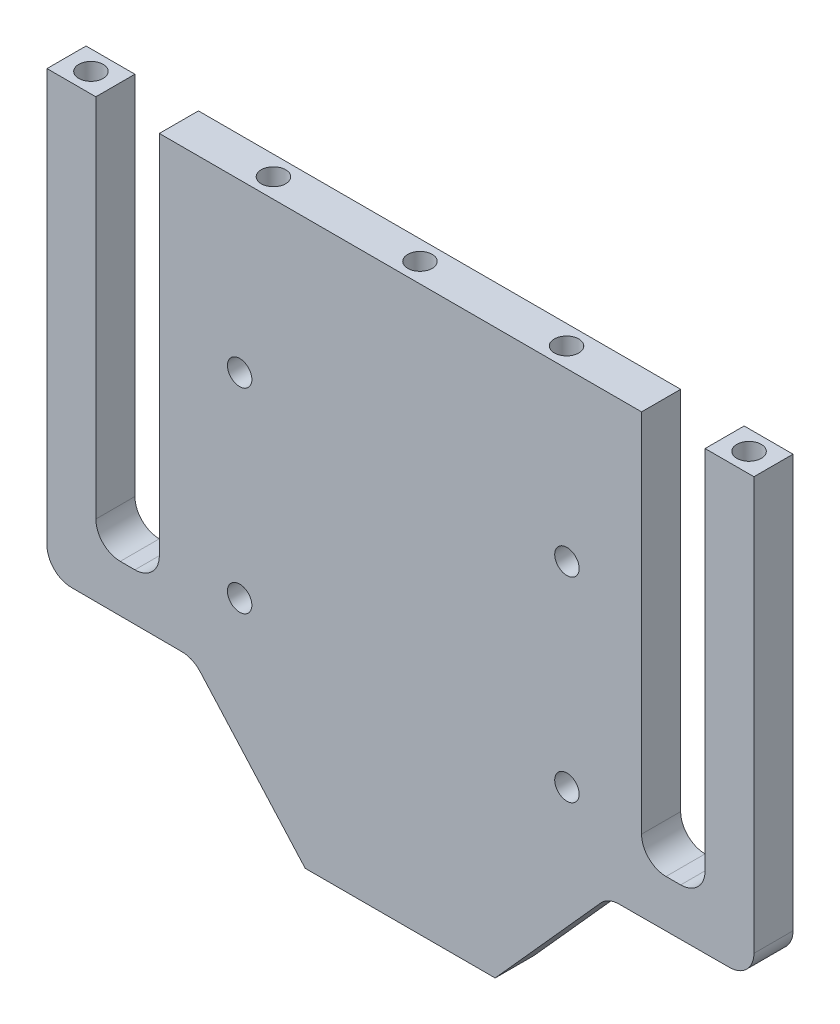
SolidWorks part; units mm, degrees
ref_plane "Front Plane" through (0, 0, 0) normal (0, 0, 1) x (1, 0, 0)
ref_plane "Top Plane" through (0, 0, 0) normal (0, 1, 0) x (1, 0, 0)
ref_plane "Right Plane" through (0, 0, 0) normal (1, 0, 0) x (0, 0, -1)
sketch "Sketch1" plane through (0, 0, 0) normal (0, 0, 1) x (1, 0, 0)
  line L4 (70, 309.9858) -> (85.2992, 309.9858)
  line L6 (43.2101, 271.7903) -> (49.7246, 305.9232)
  line L7 (42.2614, 270.1156) -> (0.0495, 220.7861)
  line L8 (0.0495, 220.7861) -> (42.9, 220.7861) construction
  line L9 (42.9, 220.7861) -> (42.9, 270.8599) construction
  line L10 (96.9829, 220.8599) -> (96.9829, 270.8599) construction
  line L11 (112.4871, 25.7747) -> (89.3829, 25.7747) construction
  line L12 (27.5129, 25.7747) -> (50.5, 25.7747) construction
  line L13 (25.2828, 25.7823) -> (2.6386, 25.8599)
  line L14 (96.6727, 271.7903) -> (90.212, 305.9159)
  line L15 (70, 329.5221) -> (70, -78.2612) construction
  line L18 (50.5, 25.7747) -> (50.5, 0) construction
  line L19 (70, 309.9858) -> (54.636, 309.9858)
  line L20 (135.9829, 220.8599) -> (96.9829, 220.8599) construction
  line L21 (139.9505, 220.7861) -> (135.9829, 220.8599) construction
  line L25 (89.3829, 25.7747) -> (89.3829, 0) construction
  line L27 (89.3829, 0) -> (50.5, 0)
  line L28 (12.6386, 35.4925) -> (15.6386, 35.4925)
  line L35 (127.3614, 35.4925) -> (124.3614, 35.4925)
  line L36 (119.3614, 213.626) -> (132.3614, 213.626)
  line L37 (119.3614, 40.4925) -> (119.3614, 213.626)
  line L38 (132.3614, 213.626) -> (132.3614, 40.4925)
  line L39 (142.3614, 214.274) -> (142.3614, 30.8599)
  line L40 (97.6215, 270.1156) -> (139.9505, 220.7861)
  line L41 (-2.3614, 214.274) -> (-2.3614, 30.8599)
  line L42 (7.6386, 213.626) -> (7.6386, 40.4925)
  line L43 (20.6386, 40.4925) -> (20.6386, 213.626)
  line L44 (20.6386, 213.626) -> (7.6386, 213.626)
  line L45 (28.9972, 24.1103) -> (50.5, 0)
  line L46 (114.7172, 25.7823) -> (137.3614, 25.8599)
  line L47 (89.3829, 0) -> (111.0028, 24.1103)
  arc A1 (42.2614, 270.1156) -> (43.2101, 271.7903) centre (38.4667, 273.3715) ccw
  arc A5 (97.6215, 270.1156) -> (96.6727, 271.7903) centre (101.4161, 273.3715) cw
  arc A8 (137.3614, 25.8599) -> (142.3614, 30.8599) centre (137.3614, 30.8599) ccw
  arc A9 (2.6386, 25.8599) -> (-2.3614, 30.8599) centre (2.6386, 30.8599) cw
  arc A10 (49.7246, 305.9232) -> (54.636, 309.9858) centre (54.636, 304.9858) cw
  arc A11 (85.2992, 309.9858) -> (90.212, 305.9159) centre (85.2992, 304.9858) cw
  arc A12 (139.9505, 220.7861) -> (142.3614, 214.274) centre (132.3614, 214.274) cw
  arc A13 (0.0495, 220.7861) -> (-2.3614, 214.274) centre (7.6386, 214.274) ccw
  arc A14 (25.2828, 25.7823) -> (28.9972, 24.1103) centre (25.2657, 20.7823) cw
  arc A15 (114.7172, 25.7823) -> (111.0028, 24.1103) centre (114.7343, 20.7823) ccw
  arc A16 (124.3614, 35.4925) -> (119.3614, 40.4925) centre (124.3614, 40.4925) cw
  arc A17 (127.3614, 35.4925) -> (132.3614, 40.4925) centre (127.3614, 40.4925) ccw
  arc A18 (12.6386, 35.4925) -> (7.6386, 40.4925) centre (12.6386, 40.4925) cw
  arc A19 (15.6386, 35.4925) -> (20.6386, 40.4925) centre (15.6386, 40.4925) ccw
  point P18 (119.3614, 35.4925)
  point P51 (132.3614, 35.4925)
  point P59 (7.6386, 35.4925)
  point P62 (20.6386, 35.4925)
  dimension "D1" = 5
  dimension "D2" = 5
  dimension "D3" = 5
  dimension "D4" = 10
  dimension "D5" = 5
  dimension "D6" = 5
extrude "Boss-Extrude1" add sketch "Sketch1" along normal blind 8
sketch "Sketch2" plane through (0, 0, 8) normal (0, 0, 1) x (1, 0, 0)
  line L2 (92.3829, 206.0089) -> (47.3829, 206.0089)
  line L8 (47.3829, 206.0089) -> (47.3829, 154.0089)
  line L9 (47.3829, 154.0089) -> (92.3829, 154.0089)
  line L10 (92.3829, 206.0089) -> (92.3829, 154.0089)
extrude "Cut-Extrude1" cut sketch "Sketch2" against normal through all contours L10 L2 L8 L9
sketch "Sketch3" plane through (0, 0, 0) normal (0, 0, -1) x (-1, 0, 0)
  line L1 (-142.3614, 115.3599) -> (2.3614, 115.3599)
  line L3 (-142.3614, 30.8599) -> (-142.3614, 214.274) construction
  line L6 (2.3614, 214.274) -> (2.3614, 30.8599) construction
split "Split1" trim tools "Sketch3" bodies to split 102 resulting bodies 104 108
ref_plane "Plane4" through (0, 115.3599, 0) normal (0, 1, 0) x (1, 0, 0)
sketch "Sketch4" plane through (0, 115.3599, 0) normal (0, -1, 0) x (-1, 0, 0)
  line L0 (-2.6386, -8) -> (-2.6386, -4)
  line L2 (2.3614, -8) -> (-7.6386, -8) construction
  circle A1 centre (-70, -4) radius 2.5
  circle A2 centre (-40, -4) radius 2.5
  circle A3 centre (-100, -4) radius 2.5
  circle A5 centre (-137.3614, -4) radius 2.5
  circle A6 centre (-2.6386, -4) radius 2.5
sketch "Sketch5" plane through (0, 115.3599, -115.3599) normal (0, -1, 0) x (1, 0, 0)
  circle A1 centre (70, 119.3599) radius 2.5
  circle A2 centre (100, 119.3599) radius 2.5
  circle A3 centre (40, 119.3599) radius 2.5
  circle A5 centre (2.6386, 119.3599) radius 2.5
  circle A6 centre (137.3614, 119.3599) radius 2.5
extrude "Cut-Extrude6" cut sketch "Sketch5" along direction (0, -1, 0) on the side of the normal blind 5.2 contours A2 | A5 | A3 | A1 | A6
extrude "Cut-Extrude7" cut sketch "Sketch4" against normal blind 5.2 contours A2 | A6 | A1 | A3 | A5
delete or keep bodies "Body-Delete/Keep 3" type delete bodies bodies 107
sketch "Sketch6" plane through (0, 0, 8) normal (0, 0, 1) x (1, 0, 0)
  circle A0 centre (37.0786, 81.1925) radius 2.5
  circle A1 centre (104.0786, 81.1925) radius 2.5
  circle A2 centre (104.0786, 41.1925) radius 2.5
  circle A3 centre (37.0786, 41.1925) radius 2.5
extrude "Cut-Extrude8" cut sketch "Sketch6" against normal through all
